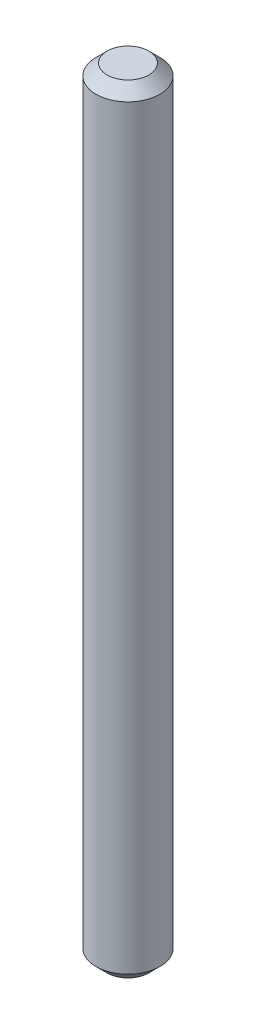
SolidWorks part; units mm, degrees
material "PBT General Purpose"
ref_plane "Front Plane" through (0, 0, 0) normal (0, 0, 1) x (1, 0, 0)
ref_plane "Top Plane" through (0, 0, 0) normal (0, 1, 0) x (1, 0, 0)
ref_plane "Right Plane" through (0, 0, 0) normal (1, 0, 0) x (0, 0, -1)
sketch "Sketch1" plane through (0, 0, 0) normal (0, 1, 0) x (1, 0, 0)
  circle A0 centre (0, 0) radius 2.875
  dimension "D1" = 5.75
extrude "Boss-Extrude1" add sketch "Sketch1" along normal mid plane 70
chamfer "Chamfer1" distance 1 angle 45 2 edges at (0, -35, 2.875) (0, 35, 2.875)
